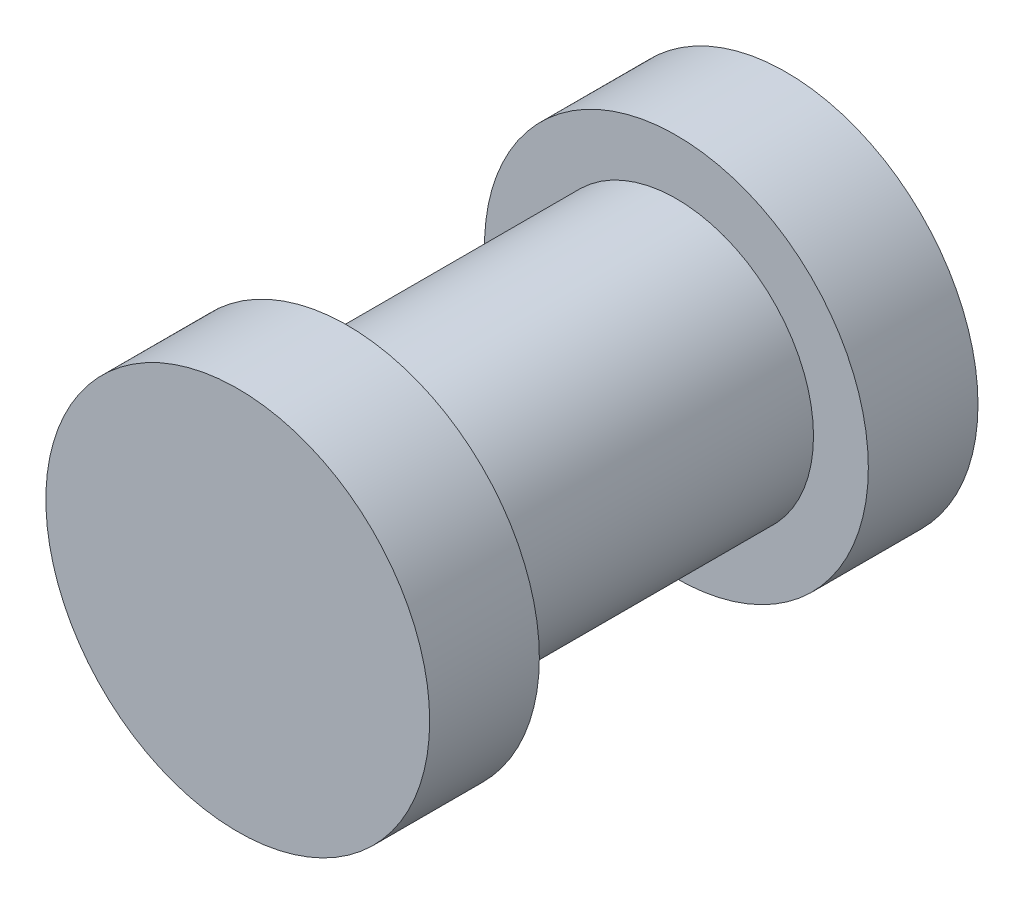
SolidWorks part; units mm, degrees
ref_plane "Front Plane" through (0, 0, 0) normal (0, 0, 1) x (1, 0, 0)
ref_plane "Top Plane" through (0, 0, 0) normal (0, 1, 0) x (1, 0, 0)
ref_plane "Right Plane" through (0, 0, 0) normal (1, 0, 0) x (0, 0, -1)
sketch "Sketch1" plane through (0, 0, 0) normal (0, 0, 1) x (1, 0, 0)
  circle A0 centre (0, 0) radius 3.5
  dimension "D1" = 7
extrude "Boss-Extrude1" add sketch "Sketch1" along normal blind 10
sketch "Sketch2" plane through (0, 0, 10) normal (0, 0, 1) x (1, 0, 0)
  circle A0 centre (0, 0) radius 3.5
  circle A1 centre (0, 0) radius 2.5
  dimension "D1" = 7
  dimension "D2" = 5
extrude "Cut-Extrude1" cut sketch "Sketch2" against normal blind 3 and the other way blind 3 from offset 5
